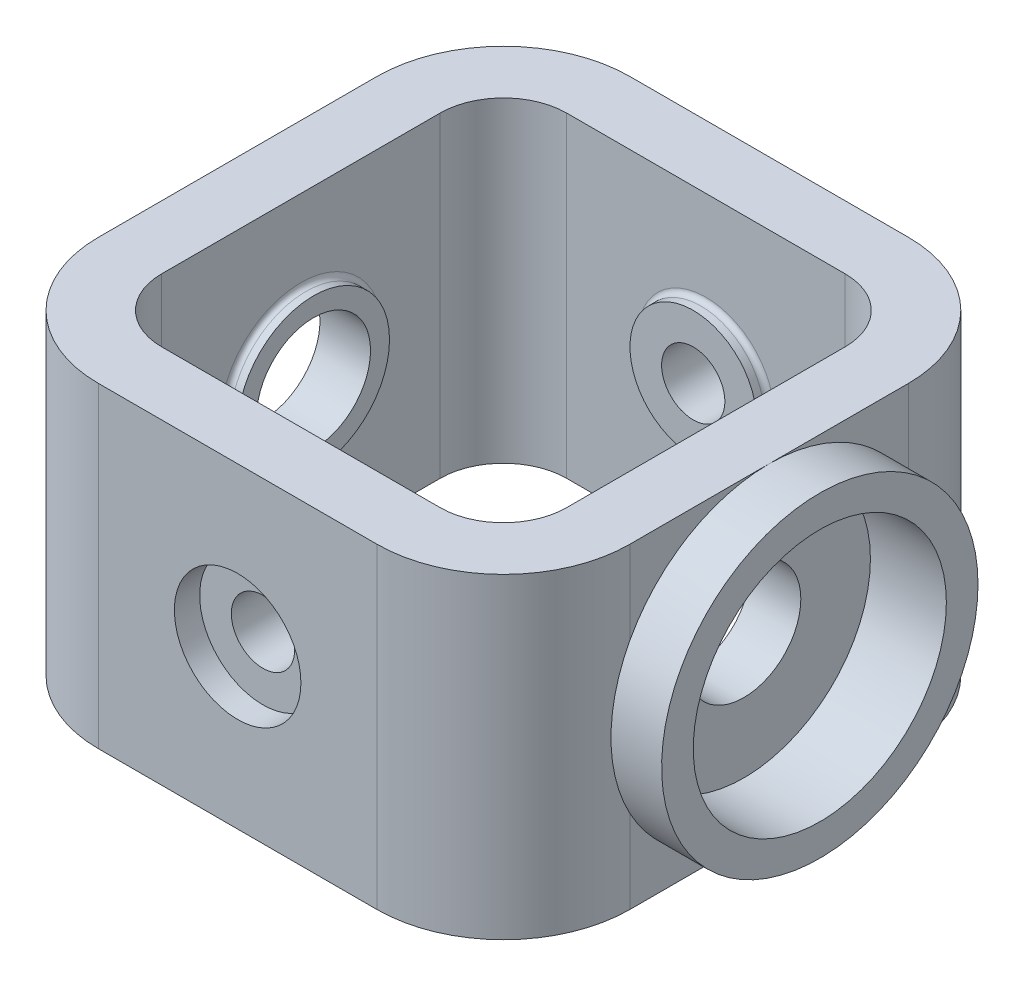
SolidWorks part; units mm, degrees
ref_plane "Plano frontal" through (0, 0, 0) normal (0, 0, 1) x (1, 0, 0)
ref_plane "Plano superior" through (0, 0, 0) normal (0, 1, 0) x (1, 0, 0)
ref_plane "Plano direito" through (0, 0, 0) normal (1, 0, 0) x (0, 0, -1)
sketch "Esboço1" plane through (0, 0, 0) normal (0, 1, 0) x (1, 0, 0)
  line L0 (-21, -11) -> (-21, 11)
  line L1 (-11, -16) -> (11, -16)
  line L2 (-16, -11) -> (-16, 11)
  line L3 (-11, 16) -> (11, 16)
  line L4 (16, -11) -> (16, 11)
  line L5 (-16, -16) -> (16, 16) construction
  line L6 (-16, 16) -> (16, -16) construction
  line L7 (-11, 21) -> (11, 21)
  line L8 (21, -11) -> (21, 11)
  line L9 (-11, -21) -> (11, -21)
  arc A0 (11, -16) -> (16, -11) centre (11, -11) ccw
  arc A1 (11, 16) -> (16, 11) centre (11, 11) cw
  arc A2 (-16, 11) -> (-11, 16) centre (-11, 11) cw
  arc A3 (-11, -16) -> (-16, -11) centre (-11, -11) cw
  arc A4 (-21, 11) -> (-11, 21) centre (-11, 11) cw
  arc A5 (11, 21) -> (21, 11) centre (11, 11) cw
  arc A6 (11, -21) -> (21, -11) centre (11, -11) ccw
  arc A7 (-11, -21) -> (-21, -11) centre (-11, -11) cw
  point P0 (0, 0)
  dimension "D2" = 5
  dimension "D1" = 32
  dimension "D3" = 5
extrude "Ressalto-extrusão1" add sketch "Esboço1" along normal mid plane 25
sketch "Esboço5" plane through (0, 0, -16) normal (0, 0, 1) x (1, 0, 0)
  line L0 (-1000, 0) -> (49000, 0) construction
  line L1 (0, -1000) -> (0, 49000) construction
  circle A0 centre (0, 0) radius 5
  dimension "D1" = 10
extrude "Ressalto-extrusão2" add sketch "Esboço5" along normal blind 1
mirror "Espelhar1" about plane through (0, 0, 0) normal (0, 0, 1) of "Ressalto-extrusão2"
sketch "Esboço6" plane through (-16, 0, 0) normal (1, 0, 0) x (0, 0, -1)
  line L0 (-1000, 0) -> (49000, 0) construction
  line L1 (0, -1000) -> (0, 49000) construction
  circle A0 centre (0, 0) radius 5
  dimension "D1" = 10
extrude "Ressalto-extrusão3" add sketch "Esboço6" along normal blind 1
mirror "Espelhar2" about plane through (0, 0, 0) normal (1, 0, 0) of "Ressalto-extrusão3"
sketch "Esboço2" plane through (0, 0, 21) normal (0, 0, 1) x (1, 0, 0)
  line L0 (-1000, 0) -> (49000, 0) construction
  line L1 (0, -1000) -> (0, 49000) construction
  circle A0 centre (0, 0) radius 2.5
  dimension "D1" = 5
extrude "Corte-extrusão1" cut sketch "Esboço2" against normal through all
sketch "Esboço3" plane through (-21, 0, 0) normal (-1, 0, 0) x (0, 0, 1)
  line L0 (-1000, 0) -> (49000, 0) construction
  line L1 (0, -1000) -> (0, 49000) construction
  circle A0 centre (0, 0) radius 2.5
  dimension "D1" = 5
extrude "Corte-extrusão2" cut sketch "Esboço3" against normal through all
sketch "Esboço7" plane through (21, 0, 0) normal (1, 0, 0) x (0, 0, -1)
  circle A0 centre (0, 0) radius 5
  dimension "D1" = 10
extrude "Corte-extrusão3" cut sketch "Esboço7" against normal blind 2
mirror "Espelhar3" about plane through (0, 0, 0) normal (1, 0, 0) of "Corte-extrusão3"
scale "Escala1" scale about centroid uniform scaling yes scale factor 0.5
sketch "Croquis4" plane through (-10.5, 0, 0) normal (-1, 0, 0) x (0, 0, 1)
  circle A0 centre (0, 0) radius 5
  dimension "D1" = 10
extrude "Cortar-Extruir3" cut sketch "Croquis4" against normal blind 1
sketch "Croquis9" plane through (-9.5, 0, 0) normal (-1, 0, 0) x (0, 0, 1)
  circle A0 centre (0, 0) radius 2.25
  dimension "D1" = 4.5
extrude "Cortar-Extruir6" cut sketch "Croquis9" against normal through all
sketch "Croquis10" plane through (8, 0, 0) normal (-1, 0, 0) x (0, 0, 1)
  circle A0 centre (0, 0) radius 2.8511
extrude "Cortar-Extruir7" cut sketch "Croquis10" along normal up to surface (16 mm away) up to face at (-8, 0, -2.5)
sketch "Croquis11" plane through (10.5, 0, 0) normal (1, 0, 0) x (0, 0, -1)
  circle A0 centre (0, 0) radius 5
  dimension "D1" = 10
extrude "Cortar-Extruir8" cut sketch "Croquis11" against normal blind 1
sketch "Croquis12" plane through (-8, 0, 0) normal (1, 0, 0) x (0, 0, -1)
  circle A0 centre (0, 0) radius 3
  circle A1 centre (0, 0) radius 2.25
  dimension "D1" = 6
sketch "Croquis13" plane through (0, 0, 10.5) normal (0, 0, 1) x (1, 0, 0)
  circle A0 centre (0, 0) radius 2.5
  circle A1 centre (0, 0) radius 1.25
  dimension "D1" = 5
extrude "Cortar-Extruir9" cut sketch "Croquis13" against normal blind 1
mirror "Simetría4" about plane through (0, 0, 0) normal (0, 0, 1) of "Cortar-Extruir9"
extrude "Saliente-Extruir3" add sketch "Croquis12" along normal blind 0.5
mirror "Simetría5" about plane through (0, 0, 0) normal (1, 0, 0) of "Saliente-Extruir3"
fillet "Redondeo1" radius 0.2 4 edges at (-8, 0, -3) (8, 0, 3) (2.5, 0, -8) (-2.5, 0, 8)
sketch "Croquis14" plane through (10.5, 0, 0) normal (1, 0, 0) x (0, 0, -1)
  line L1 (-5.5, 6.25) -> (5.5, 6.25)
  circle A0 centre (0, 0) radius 5
  circle A1 centre (0, 0) radius 6.25
extrude "Saliente-Extruir5" add sketch "Croquis14" along normal blind 2 contours A1 | A0
